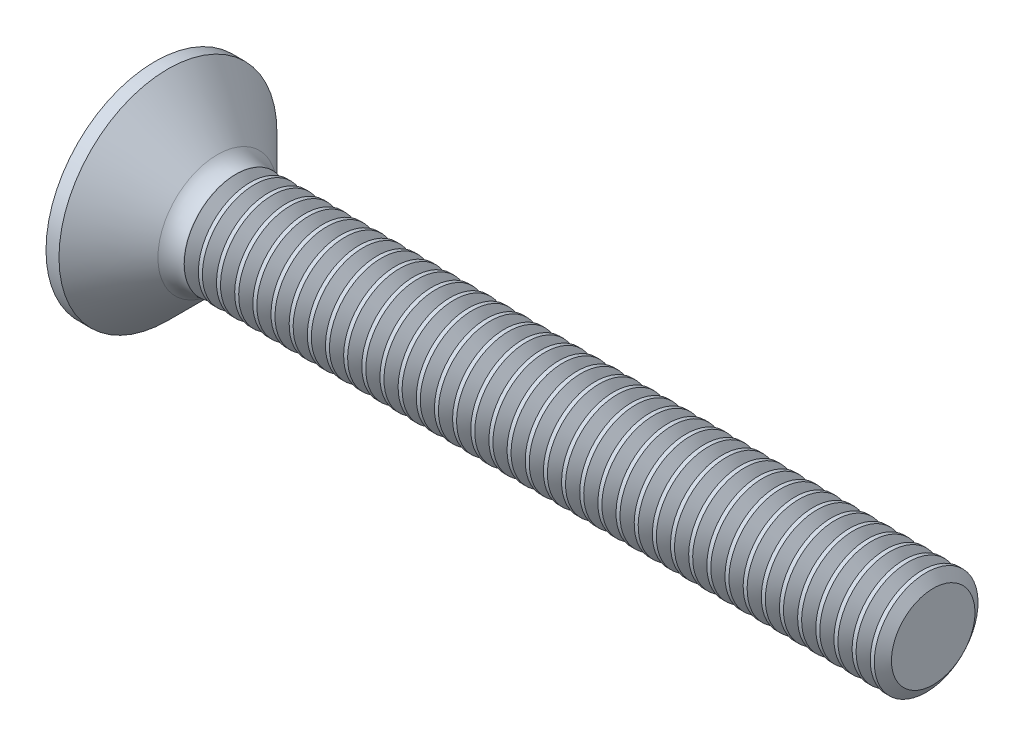
SolidWorks part; units mm, degrees
ref_plane "Plane1" through (0, 0, 0) normal (0, 0, 1) x (1, 0, 0)
ref_plane "Plane2" through (0, 0, 0) normal (0, 1, 0) x (1, 0, 0)
ref_plane "Plane3" through (0, 0, 0) normal (1, 0, 0) x (0, 0, -1)
other "Configuration Table"
sketch "BodySke" plane through (0, 0, 0) normal (0, 0, 1) x (1, 0, 0)
  line L0 (0, 0) -> (31, 0)
  line L1 (31, 0) -> (31, 2)
  line L2 (31, 2) -> (3.7, 2)
  line L3 (1.5, -4.2) -> (3.7, -2) construction
  line L4 (-15.875, 0) -> (82.55, 0) construction
  line L5 (1.5, 4.2) -> (3.7, 2)
  line L6 (4.4, 5.175) -> (4.4, -10.7) construction
  line L7 (1, 2.7793) -> (1, -13.0957) construction
  line L8 (1.5, 4.2) -> (1, 4.2)
  arc A0 (0, 0) -> (1, 4.2) centre (9.32, 0) cw
  dimension "Head_ang" = 90
  dimension "Diameter" = 4
  dimension "Advance" = 0.7
  dimension "Thread_nom" = 30
  dimension "Oval_ht" = 1
  dimension "Side_ht" = 2.7
  dimension "Head_dia" = 8.4
  dimension "Length" = 30
revolve "Base-Revolve" add sketch "BodySke" angle 360 about L4
cosmetic thread "ThreadCosmetic" parameters "Thread_length"=26.6, "Thread_minor"=3.22
fillet "Fillet1" radius 1 1 edges at (3.7, 0, 2)
sketch "Sketch3" plane through (0, 0, 0) normal (1, 0, 0) x (0, 0, -1)
  line L0 (0.515, -2.5) -> (-0.515, -2.5)
  line L1 (0.515, -2.5) -> (0.515, 2.5)
  line L2 (-0.515, 2.5) -> (0.515, 2.5)
  line L3 (-0.515, 2.5) -> (-0.515, -2.5)
  dimension "Cross_width" = 1.03
  dimension "D1" = 0.515
  dimension "Cross_dia" = 5
  dimension "D2" = 2.5
ref_plane "Plane4" through (3.1, 0, 0) normal (1, 0, 0) x (0, 0, -1)
sketch "Sketch4" plane through (3.1, 0, 0) normal (1, 0, 0) x (0, 0, -1)
  line L0 (0.515, -0.9544) -> (-0.515, -0.9544)
  line L1 (0.515, -0.9544) -> (0.515, 0.9544)
  line L2 (-0.515, 0.9544) -> (0.515, 0.9544)
  line L3 (-0.515, 0.9544) -> (-0.515, -0.9544)
  dimension "D1" = 1.03
  dimension "D2" = 1.9088
  dimension "D3" = 0.515
  dimension "D4" = 0.9544
loft "Recess" cut profiles "Sketch3", "Sketch4"
pattern_circular "RecPat" count 2 every 90 about axis through (0, 0, 0) along (1, 0, 0) of "Recess"
sketch "RecCorSke" plane through (0, 0, 0) normal (0, 0, 1) x (1, 0, 0)
  line L0 (-3.175, 0) -> (15.875, 0) construction
  line L2 (0, 0) -> (0, 1.0678)
  line L3 (0, 1.0678) -> (3.1, 0.851)
  line L4 (3.1, 0.851) -> (3.3765, 0)
  line L5 (3.3765, 0) -> (0, 0)
  dimension "Diameter" = 1.702
  dimension "Depth" = 3.1
  dimension "Draft_angle" = 4
  dimension "Bottom_angle" = 18
revolve "RecessCore" cut sketch "RecCorSke" angle 360 about L0
sketch "ThdSchSke" plane through (0, 0, 0) normal (0, 0, 1) x (1, 0, 0)
  line L0 (4.4, -1.61) -> (4.1269, -2)
  line L1 (4.4, -1.61) -> (4.6731, -2)
  line L2 (4.6731, -2) -> (4.6731, -2.5)
  line L3 (-3.175, 0) -> (5.1513, 0) construction
  line L5 (4.6731, -2.5) -> (4.1269, -2.5)
  line L6 (4.1269, -2.5) -> (4.1269, -2)
  dimension "Diameter" = 4
  dimension "SideAngle" = 55
  dimension "VeeAngle" = 70
  dimension "Thread_minor" = 3.22
  dimension "Overcut" = 5
  dimension "Start" = 4.4
revolve "ThreadSchematic" cut sketch "ThdSchSke" angle 360 about L3
pattern_linear "ThdSchPat" count 39 spacing 0.7 along (1, 0, 0) of "ThreadSchematic"
equation "\"D1@Sketch3\" = \"Cross_width@Sketch3\" / 2"
equation "\"D2@Sketch3\" = \"Cross_dia@Sketch3\" / 2"
equation "\"Depth@RecCorSke\" = \"Cross_depth@Plane4\""
equation "\"D1@Sketch4\" = \"Cross_width@Sketch3\""
equation "\"D2@Sketch4\" = \"Cross_dia@Sketch3\" - 2.0 * \"Cross_depth@Plane4\" * tan(26.5  * 0.017453292)"
equation "\"D3@Sketch4\" = \"D1@Sketch4\" / 2"
equation "\"D4@Sketch4\" = \"D2@Sketch4\" / 2"
equation "\"Thread_length@ThreadCosmetic\" = ((sgn( (\"Length@BodySke\" - \"Advance@BodySke\" - \"Side_ht@BodySke\" ) - \"Thread_nom@BodySke\" )-1)*( (\"Length@BodySke\" - \"Advance@BodySke\" - \"Side_ht@BodySke\" ) - \"Thread_nom@BodySke\" ))/-2+ \"Thread_nom@BodySke\""
equation "\"Thread_minor@ThdSchSke\" = \"Thread_minor@ThreadCosmetic\""
equation "\"Diameter@ThdSchSke\" = \"Diameter@BodySke\""
equation "\"Overcut@ThdSchSke\" = \"Diameter@BodySke\" * 1.25"
equation "\"Start@ThdSchSke\" = \"Oval_ht@BodySke\" + \"Length@BodySke\" - \"Thread_length@ThreadCosmetic\"  '---Countersunk---"
equation "\"Num_threads@ThdSchPat\" = int( \"Thread_length@ThreadCosmetic\" / \"Advance@BodySke\" + 0.999 )  + 1"
equation "\"Advance@ThdSchPat\" = \"Thread_length@ThreadCosmetic\" /  (\"Num_threads@ThdSchPat\" - 1) 'relax it"
